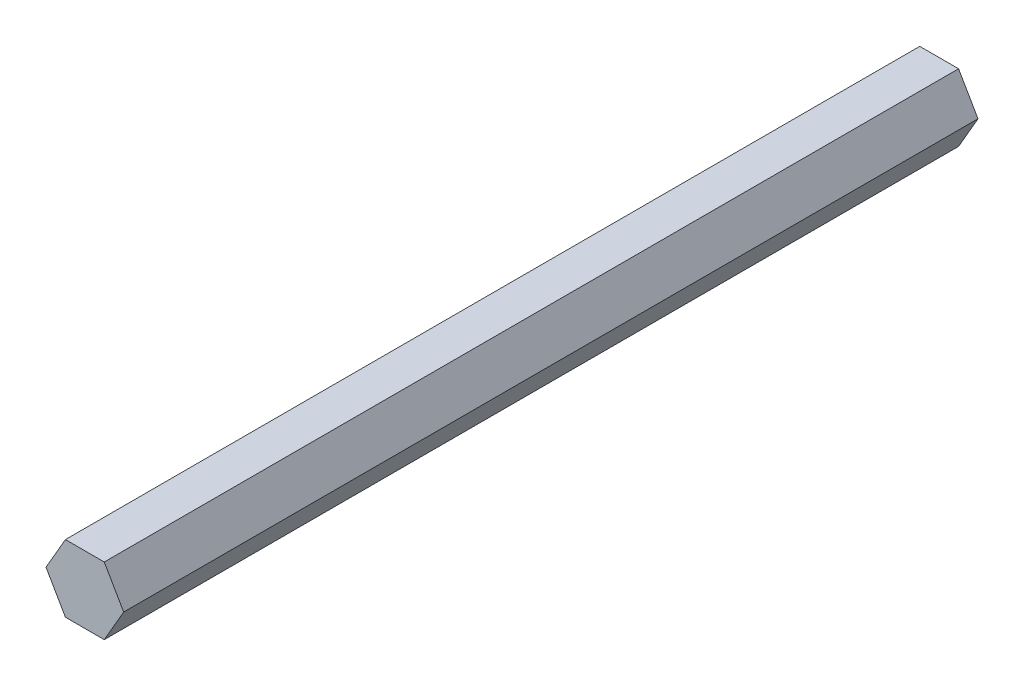
SolidWorks part; units mm, degrees
ref_plane "Front Plane" through (0, 0, 0) normal (0, 0, 1) x (1, 0, 0)
ref_plane "Top Plane" through (0, 0, 0) normal (0, 1, 0) x (1, 0, 0)
ref_plane "Right Plane" through (0, 0, 0) normal (1, 0, 0) x (0, 0, -1)
sketch "Sketch1" plane through (0, 0, 0) normal (0, 0, 1) x (1, 0, 0)
  line L1 (1.7321, 0) -> (0.866, 1.5)
  line L2 (0.866, 1.5) -> (-0.866, 1.5)
  line L3 (-0.866, 1.5) -> (-1.7321, 0)
  line L4 (-1.7321, 0) -> (-0.866, -1.5)
  line L5 (-0.866, -1.5) -> (0.866, -1.5)
  line L6 (0.866, -1.5) -> (1.7321, 0)
  circle A0 centre (0, 0) radius 1.5 construction
  dimension "D1" = 3
extrude "Boss-Extrude1" add sketch "Sketch1" along normal blind 38.1
